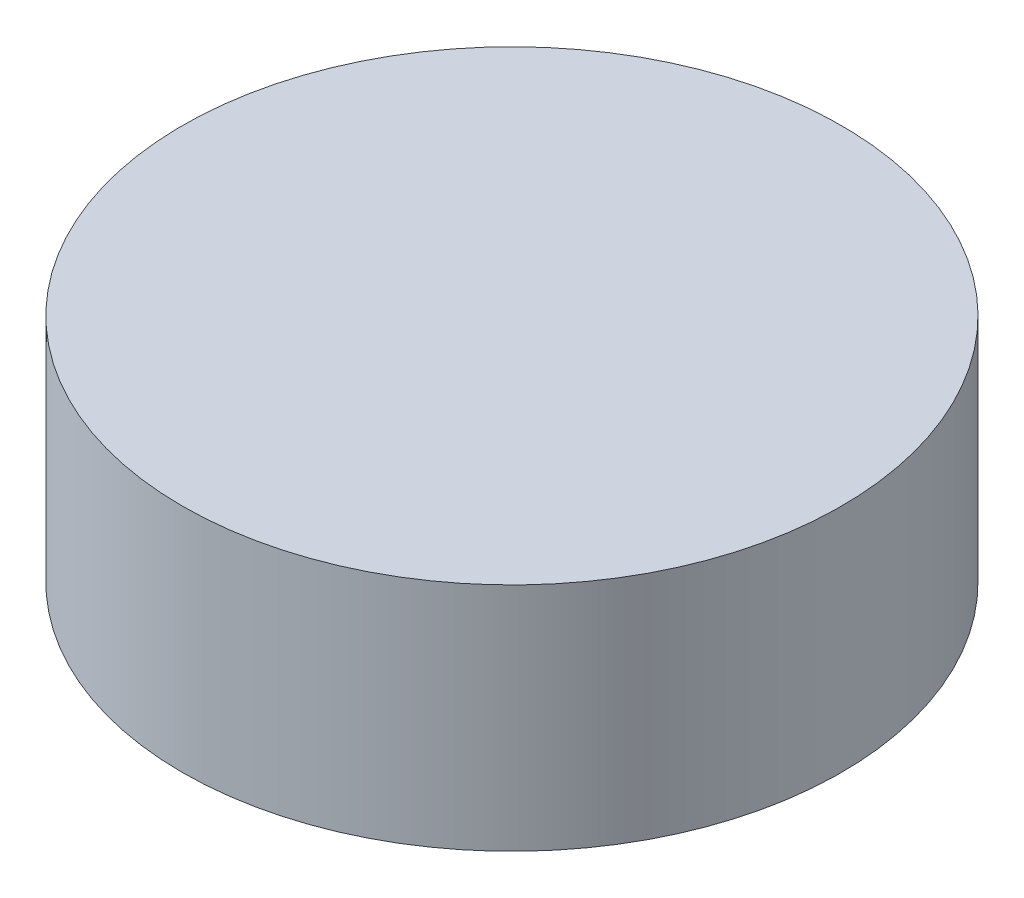
SolidWorks part; units mm, degrees
ref_plane "Plan de face" through (0, 0, 0) normal (0, 0, 1) x (1, 0, 0)
ref_plane "Plan de dessus" through (0, 0, 0) normal (0, 1, 0) x (1, 0, 0)
ref_plane "Plan de droite" through (0, 0, 0) normal (1, 0, 0) x (0, 0, -1)
sketch "Esquisse1" plane through (0, 0, 0) normal (0, 1, 0) x (1, 0, 0)
  circle A0 centre (0, 0) radius 10
  dimension "D1" = 20
extrude "Boss.-Extru.1" add sketch "Esquisse1" along normal blind 7
